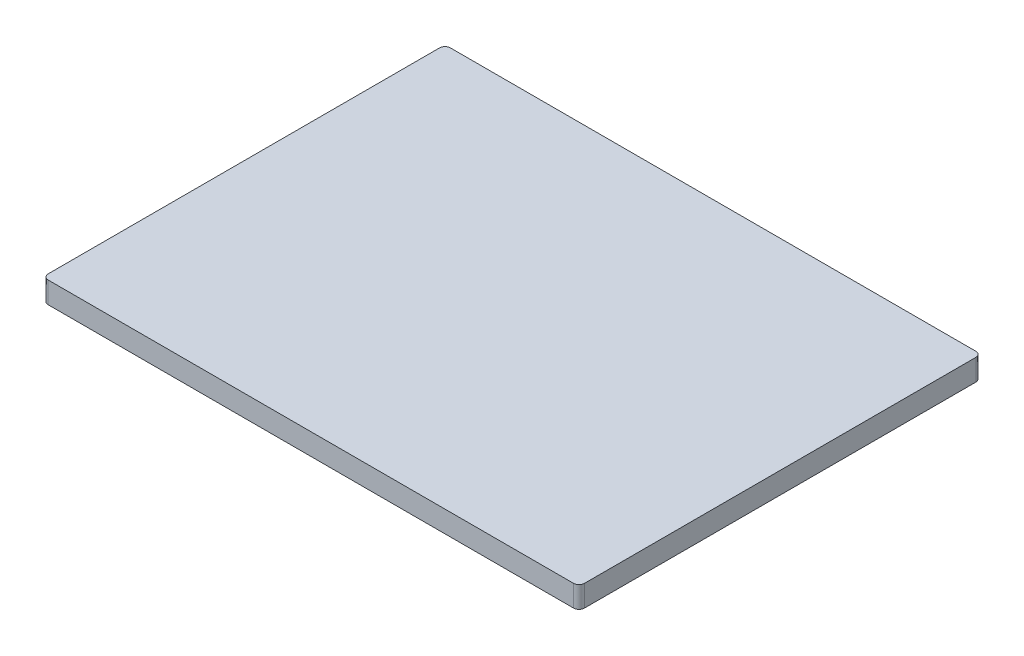
SolidWorks part; units mm, degrees
ref_plane "Alzado" through (0, 0, 0) normal (0, 0, 1) x (1, 0, 0)
ref_plane "Planta" through (0, 0, 0) normal (0, 1, 0) x (1, 0, 0)
ref_plane "Vista lateral" through (0, 0, 0) normal (1, 0, 0) x (0, 0, -1)
sketch "Croquis1" plane through (0, 0, 0) normal (0, 1, 0) x (1, 0, 0)
  line L1 (-100, -75) -> (100, -75)
  line L2 (-100, -75) -> (-100, 75)
  line L3 (-100, 75) -> (100, 75)
  line L4 (100, -75) -> (100, 75)
  line L5 (-100, -75) -> (100, 75) construction
  line L6 (-100, 75) -> (100, -75) construction
  point P0 (0, 0)
  dimension "D1" = 150
  dimension "D2" = 200
extrude "Saliente-Extruir1" add sketch "Croquis1" along normal blind 8
fillet "Redondeo1" radius 2 4 edges at (-100, 4, -75) (100, 4, -75) (100, 4, 75) (-100, 4, 75)
